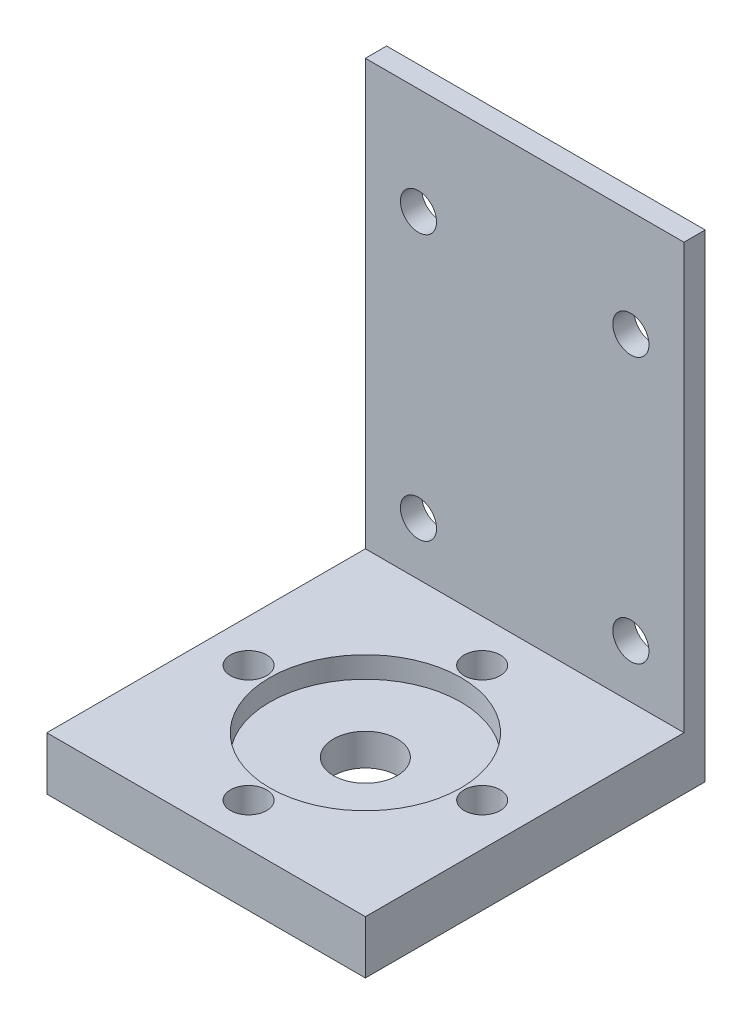
SolidWorks part; units mm, degrees
ref_plane "Front Plane" through (0, 0, 0) normal (0, 0, 1) x (1, 0, 0)
ref_plane "Top Plane" through (0, 0, 0) normal (0, 1, 0) x (1, 0, 0)
ref_plane "Right Plane" through (0, 0, 0) normal (1, 0, 0) x (0, 0, -1)
sketch "Sketch2" plane through (0, 0, 0) normal (1, 0, 0) x (0, 0, -1)
  line L0 (0, 0) -> (32, 0)
  line L1 (32, 0) -> (32, 45)
  line L2 (32, 45) -> (30, 45)
  line L3 (30, 45) -> (30, 5)
  line L4 (30, 5) -> (0, 5)
  line L5 (0, 5) -> (0, 0)
  dimension "D1" = 2
  dimension "D2" = 30
  dimension "D3" = 5
  dimension "D4" = 40
extrude "Boss-Extrude1" add sketch "Sketch2" along normal blind 30
sketch "Sketch3" plane through (0, 5, 0) normal (0, 1, 0) x (1, 0, 0)
  line L0 (0, 0) -> (30, 30) construction
  circle A0 centre (15, 15) radius 9
  circle A1 centre (15, 15) radius 3
  dimension "D1" = 18
  dimension "D2" = 6
extrude "Cut-Extrude1" cut sketch "Sketch3" against normal blind 2
sketch "Sketch7" plane through (0, 5, 0) normal (0, 1, 0) x (1, 0, 0)
  circle A0 centre (15, 15) radius 3
extrude "Cut-Extrude2" cut sketch "Sketch7" against normal through all
sketch "Sketch8" plane through (0, 3, 0) normal (0, 1, 0) x (1, 0, 0)
  line L0 (0, 15) -> (30, 15) construction
  line L1 (0, 30) -> (0, 0) construction
  line L2 (30, 30) -> (30, 0) construction
  line L3 (15, 30) -> (15, 0) construction
  line L4 (30, 30) -> (0, 30) construction
  line L5 (30, 0) -> (0, 0) construction
  circle A0 centre (4, 15) radius 1.7
  circle A1 centre (26, 15) radius 1.7
  circle A2 centre (15, 4) radius 1.7
  circle A3 centre (15, 26) radius 1.7
  circle A5 centre (15, 15) radius 11
  dimension "D1" = 3.4
  dimension "D5" = 22
extrude "Cut-Extrude3" cut sketch "Sketch8" against normal through all and the other way blind 2 contours A0 | A3 | A1 | A2
sketch "Sketch9" plane through (0, 0, -30) normal (0, 0, 1) x (1, 0, 0)
  line L0 (30, 0) -> (0, 0) construction
  line L1 (30, 45) -> (0, 45) construction
  line L2 (30, 45) -> (30, 5) construction
  circle A0 centre (5, 35) radius 1.7
  circle A1 centre (25, 35) radius 1.7
  circle A2 centre (25, 10) radius 1.7
  circle A3 centre (5, 10) radius 1.7
  dimension "D1" = 3.4
  dimension "D2" = 5
  dimension "D6" = 3.4
  dimension "D3" = 10
  dimension "D4" = 10
  dimension "D5" = 25
  dimension "D7" = 10
  dimension "D8" = 10
  dimension "D9" = 25
  dimension "D10" = 5
extrude "Cut-Extrude4" cut sketch "Sketch9" against normal through all
equation "\"FT1 L\"= 30mm"
equation "\"FT1 H\"= 30mm"
equation "\"FT1 b\"= 5mm"
equation "\"FT2 H\"= 40mm"
equation "\"FT2 b\"= 2mm"
equation "\"Bolt holes\"= 3.4mm"
equation "\"FT1 Shaft hole\"= 6mm"
equation "\"FT1 Base hole\"= 18mm"
equation "\"D1@Sketch2\"=\"FT2 b\""
equation "\"D2@Sketch2\"=\"FT1 H\""
equation "\"D3@Sketch2\"=\"FT1 b\""
equation "\"D4@Sketch2\"=\"FT2 H\""
equation "\"D1@Boss-Extrude1\"=\"FT1 L\""
equation "\"D1@Sketch3\"=\"FT1 Base hole\""
equation "\"D2@Sketch3\"=\"FT1 Shaft hole\""
equation "\"D1@Sketch8\"=\"Bolt holes\""
